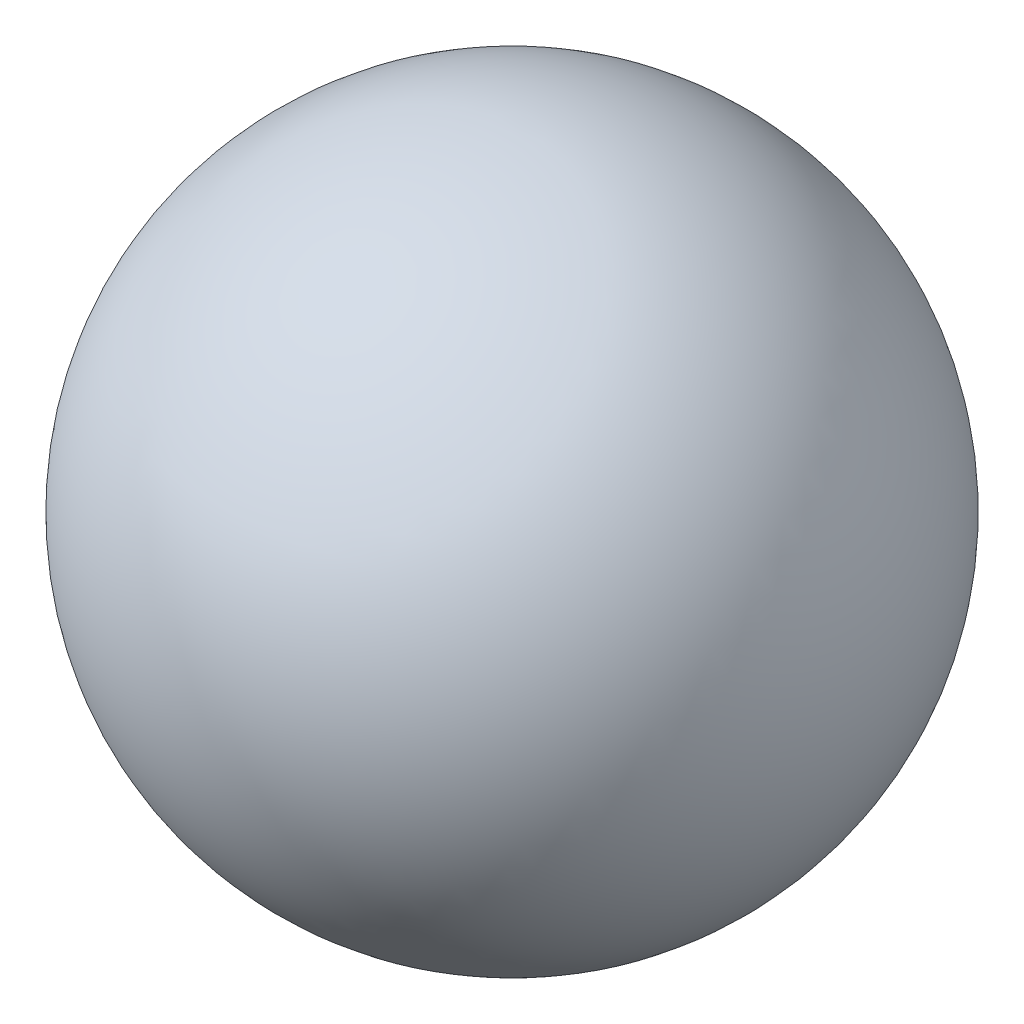
SolidWorks part; units mm, degrees
ref_plane "Front Plane" through (0, 0, 0) normal (0, 0, 1) x (1, 0, 0)
ref_plane "Top Plane" through (0, 0, 0) normal (0, 1, 0) x (1, 0, 0)
ref_plane "Right Plane" through (0, 0, 0) normal (1, 0, 0) x (0, 0, -1)
sketch "Sketch1" plane through (0, 0, 0) normal (0, 0, 1) x (1, 0, 0)
  line L0 (0, 12.4723) -> (0, -12.4723) construction
  line L1 (0, 6) -> (0, -6)
  arc A0 (0, 6) -> (0, -6) centre (0, 0) cw
  point P4 (0, 0)
  point P8 (0, 0)
  dimension "D2" = 6
  dimension "D1" = 12
revolve "Revolve1" add sketch "Sketch1" angle 360 about L0
scale "Scale1" scale about centroid uniform scaling yes scale factor 0.5
scale "Scale2" scale about centroid uniform scaling yes scale factor 1.25
scale "Scale3" scale about centroid uniform scaling yes scale factor 1.1
